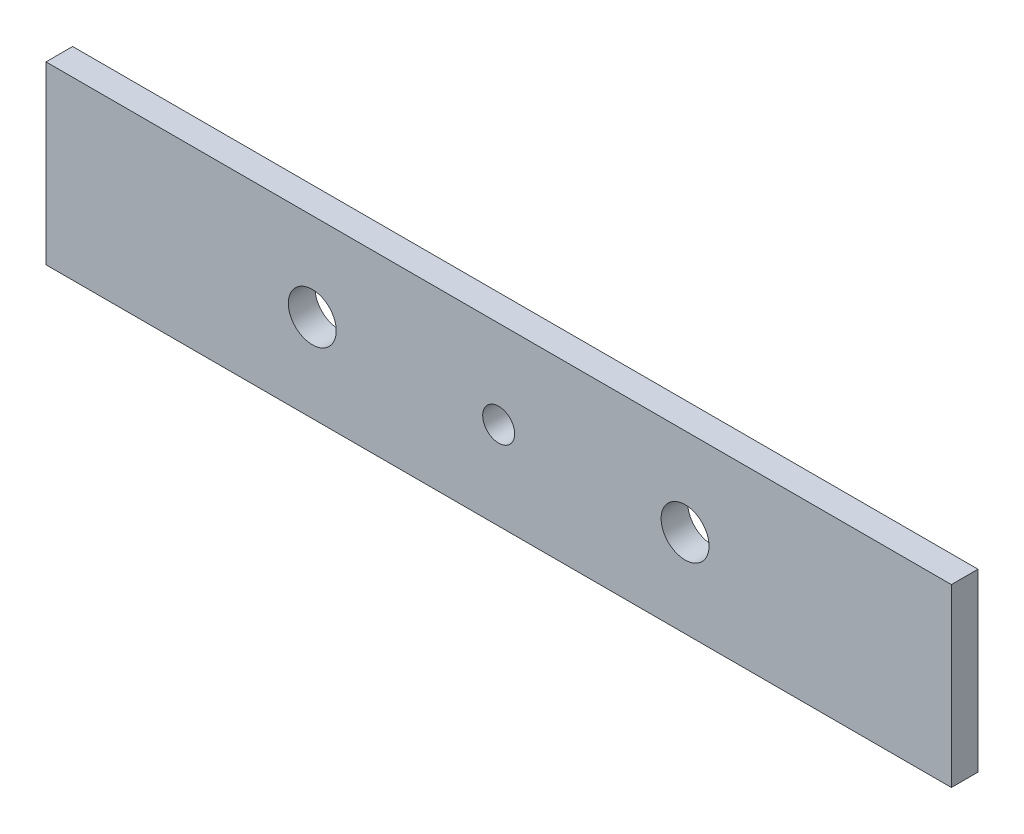
SolidWorks part; units mm, degrees
ref_plane "Front Plane" through (0, 0, 0) normal (0, 0, 1) x (1, 0, 0)
ref_plane "Top Plane" through (0, 0, 0) normal (0, 1, 0) x (1, 0, 0)
ref_plane "Right Plane" through (0, 0, 0) normal (1, 0, 0) x (0, 0, -1)
sketch "Sketch1" plane through (0, 0, 0) normal (0, 1, 0) x (1, 0, 0)
  line L1 (0, 0) -> (170, 0)
  line L2 (0, 0) -> (0, 5)
  line L3 (0, 5) -> (170, 5)
  line L4 (170, 0) -> (170, 5)
  dimension "D1" = 170
  dimension "D2" = 5
extrude "Boss-Extrude1" add sketch "Sketch1" along normal blind 33
sketch "Sketch2" plane through (0, 0, 0) normal (0, 0, 1) x (1, 0, 0)
  line L0 (0, 16.5) -> (170, 16.5) construction
  line L1 (0, 33) -> (0, 0) construction
  line L2 (170, 33) -> (170, 0) construction
  line L3 (85, 33) -> (85, 0) construction
  line L4 (0, 33) -> (170, 33) construction
  line L5 (0, 0) -> (170, 0) construction
  line L6 (50, 33) -> (50, 0) construction
  line L7 (120, 33) -> (120, 0) construction
  circle A0 centre (85, 16.5) radius 3
  circle A2 centre (120, 16.5) radius 4.5
  circle A3 centre (50, 16.5) radius 4.5
  dimension "D1" = 50
  dimension "D2" = 50
extrude "Cut-Extrude1" cut sketch "Sketch2" against normal blind 29
